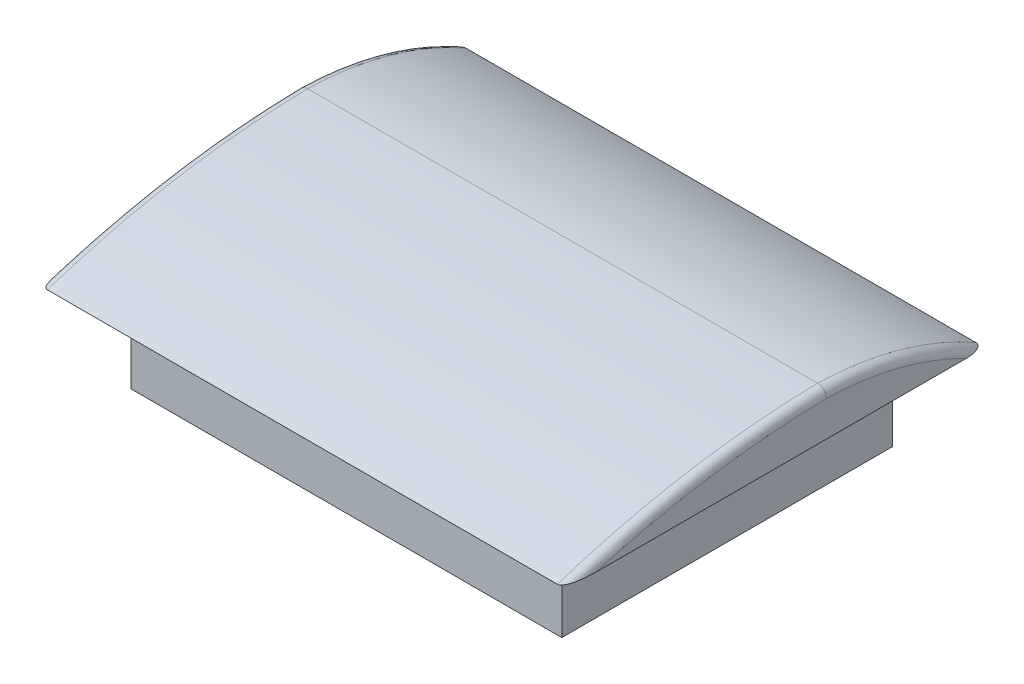
SolidWorks part; units mm, degrees
ref_plane "Front Plane" through (0, 0, 0) normal (0, 0, 1) x (1, 0, 0)
ref_plane "Top Plane" through (0, 0, 0) normal (0, 1, 0) x (1, 0, 0)
ref_plane "Right Plane" through (0, 0, 0) normal (1, 0, 0) x (0, 0, -1)
sketch "Sketch1" plane through (0, 0, 0) normal (0, 1, 0) x (1, 0, 0)
  line L0 (0, -55) -> (0, 55) construction
  line L1 (-62.23, -50.8) -> (62.23, -50.8)
  line L2 (-62.23, -50.8) -> (-62.23, 44.704)
  line L3 (-62.23, 44.704) -> (62.23, 44.704)
  line L4 (62.23, -50.8) -> (62.23, 44.704)
  line L5 (-55, 0) -> (55, 0) construction
  dimension "D1" = 95.504
  dimension "D2" = 124.46
  dimension "D3" = 62.23
  dimension "D4" = 50.8
extrude "Boss-Extrude1" add sketch "Sketch1" along normal blind 25.4
sketch "Sketch3" plane through (0, 0, 0) normal (1, 0, 0) x (0, 0, -1)
  line L0 (-50.8, 25.4) -> (-63.5, 25.4)
  line L1 (44.704, 25.4) -> (57.404, 25.4)
  line L2 (11.684, 25.4) -> (11.684, 38.1)
  line L3 (-50.8, 25.4) -> (44.704, 25.4) construction
  line L4 (44.704, 25.4) -> (44.704, 0) construction
  line L5 (11.684, 25.4) -> (-50.8, 25.4)
  line L6 (11.684, 25.4) -> (44.704, 25.4)
  arc A0 (-63.5, 25.4) -> (11.684, 38.1) centre (15.9188, -215.8647) cw
  arc A1 (11.684, 38.1) -> (57.404, 25.4) centre (9.5269, -58.3114) cw
  dimension "D5" = 254
  dimension "D6" = 96.4355
  dimension "D1" = 12.7
  dimension "D2" = 12.7
  dimension "D3" = 12.7
  dimension "D4" = 33.02
extrude "Boss-Extrude2" add sketch "Sketch3" along normal blind 76.2 and the other way blind 76.2 contours A1 L2 L6 L1 | A0 L0 L5 L2
sketch "Sketch4" plane through (0, 0, 0) normal (0, -1, 0) x (1, 0, 0)
  line L0 (-62.23, -44.704) -> (-62.23, 50.8) construction
  line L1 (-57.15, -39.624) -> (57.15, -39.624)
  line L2 (-57.15, -39.624) -> (-57.15, 45.72)
  line L3 (-57.15, 45.72) -> (57.15, 45.72)
  line L4 (57.15, -39.624) -> (57.15, 45.72)
  line L5 (-62.23, 50.8) -> (62.23, 50.8) construction
  line L6 (62.23, 50.8) -> (62.23, -44.704) construction
  line L7 (62.23, -44.704) -> (-62.23, -44.704) construction
  dimension "D1" = 5.08
  dimension "D2" = 5.08
  dimension "D3" = 5.08
  dimension "D4" = 5.08
extrude "Cut-Extrude1" cut sketch "Sketch4" against normal blind 25.4
fillet "Fillet3" radius 2.54 4 edges at (-76.2, 34.606, -35.3373) (76.2, 34.606, -35.3373) (76.2, 34.5873, 26.3873) (-76.2, 34.5873, 26.3873)
